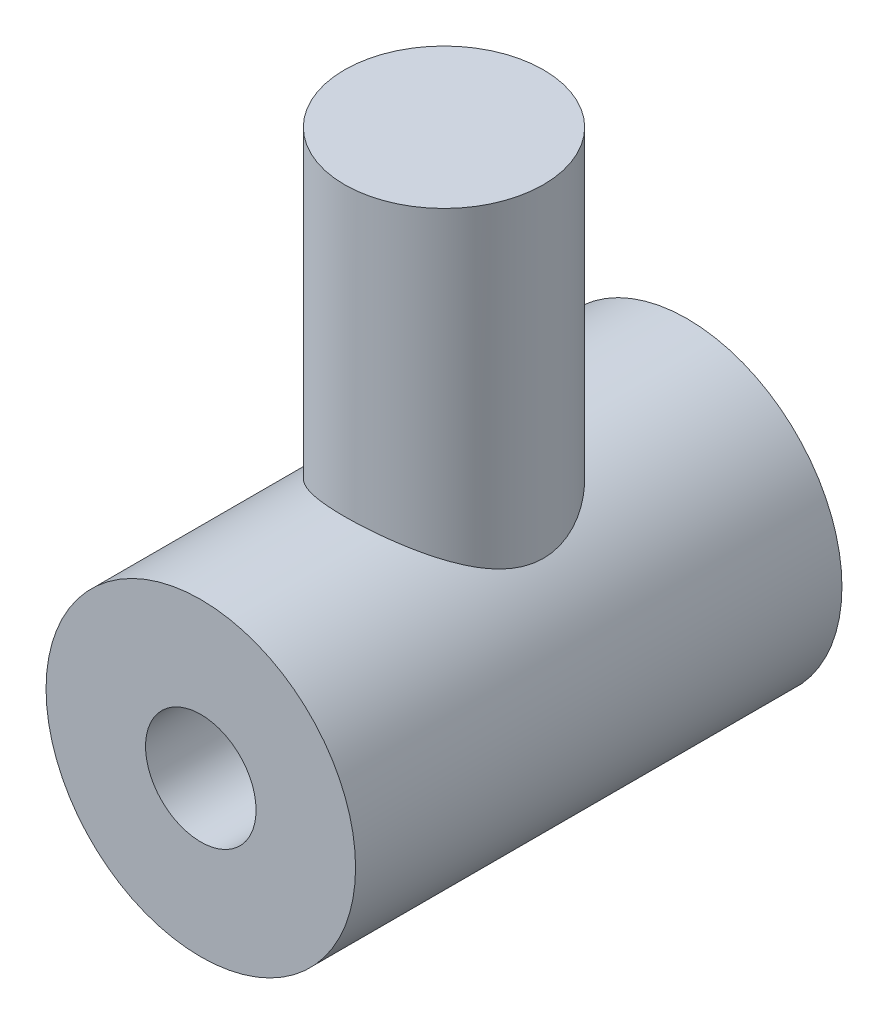
SolidWorks part; units mm, degrees
ref_plane "Front Plane" through (0, 0, 0) normal (0, 0, 1) x (1, 0, 0)
ref_plane "Top Plane" through (0, 0, 0) normal (0, 1, 0) x (1, 0, 0)
ref_plane "Right Plane" through (0, 0, 0) normal (1, 0, 0) x (0, 0, -1)
sketch "Sketch1" plane through (0, 0, 0) normal (0, 0, 1) x (1, 0, 0)
  circle A0 centre (0, 0) radius 14
  dimension "D1" = 28
extrude "Boss-Extrude1" add sketch "Sketch1" along normal blind 44
sketch "Sketch2" plane through (0, 0, 0) normal (0, 1, 0) x (1, 0, 0)
  line L0 (0, 0) -> (0, -44) construction
  line L1 (-14, -44) -> (14, -44) construction
  circle A0 centre (0, -22) radius 9
  dimension "D1" = 18
extrude "Boss-Extrude2" add sketch "Sketch2" along normal blind 40
sketch "Sketch3" plane through (0, 0, 44) normal (0, 0, 1) x (1, 0, 0)
  circle A0 centre (0, 0) radius 5
  dimension "D1" = 10
extrude "Cut-Extrude1" cut sketch "Sketch3" against normal through all
